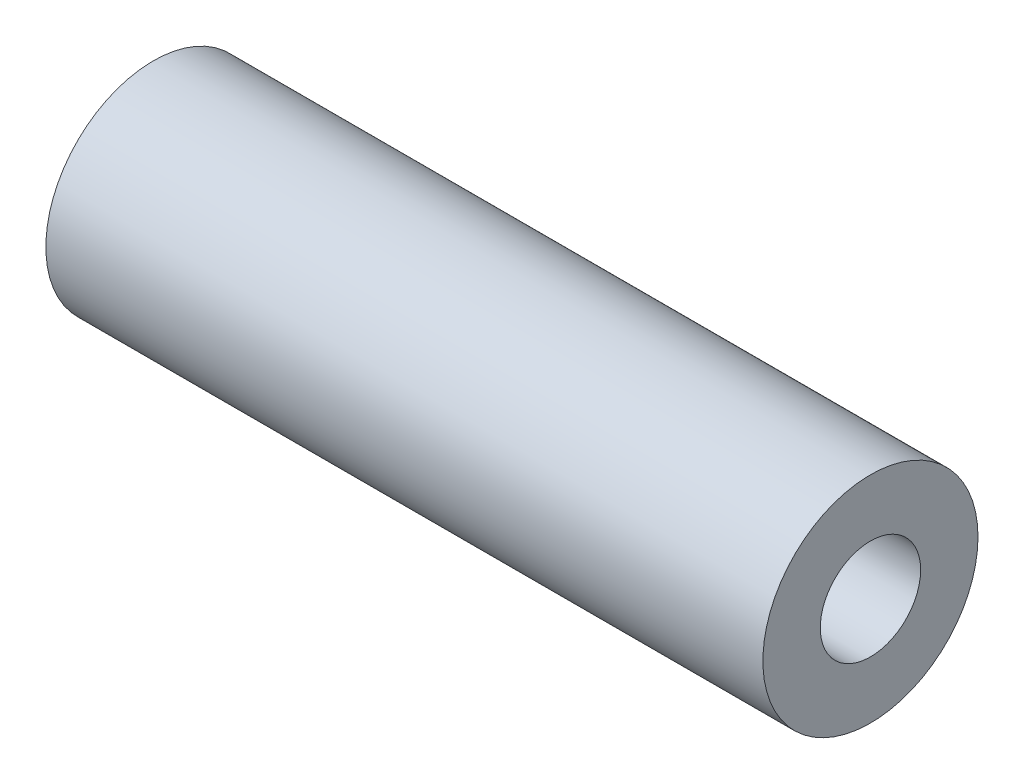
SolidWorks part; units mm, degrees
material "6061-T6 (SS)"
ref_plane "前视基准面" through (0, 0, 0) normal (0, 0, 1) x (1, 0, 0)
ref_plane "上视基准面" through (0, 0, 0) normal (0, 1, 0) x (1, 0, 0)
ref_plane "右视基准面" through (0, 0, 0) normal (1, 0, 0) x (0, 0, -1)
other "Configuration Table"
sketch "草图1" plane through (0, 0, 0) normal (1, 0, 0) x (0, 0, -1)
  circle A0 centre (0, 0) radius 2.1
  circle A1 centre (0, 0) radius 4.5
  dimension "D1" = 4.2
  dimension "D2" = 9
extrude "凸台-拉伸1" add sketch "草图1" along normal blind 30
